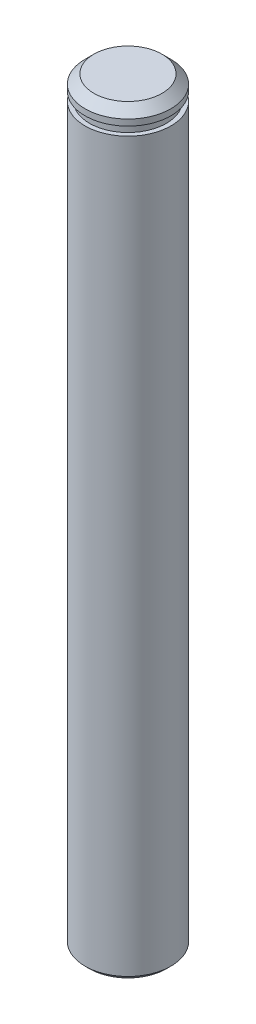
SolidWorks part; units mm, degrees
ref_plane "Front Plane" through (0, 0, 0) normal (0, 0, 1) x (1, 0, 0)
ref_plane "Top Plane" through (0, 0, 0) normal (0, 1, 0) x (1, 0, 0)
ref_plane "Right Plane" through (0, 0, 0) normal (1, 0, 0) x (0, 0, -1)
sketch "Sketch1" plane through (0, 0, 0) normal (0, 0, 1) x (1, 0, 0)
  line L0 (0, 41.165) -> (0, -40.665)
  line L1 (0, 41.165) -> (-0.5, 41.165)
  line L2 (-0.5, 41.165) -> (-0.5, 42.145)
  line L3 (-0.5, 42.145) -> (0, 42.145)
  line L4 (0, 42.145) -> (0, 42.835)
  line L5 (0, 42.835) -> (-1, 43.835)
  line L6 (-1, 43.835) -> (-4.825, 43.835)
  line L7 (-4.825, 43.835) -> (-4.825, -41.165)
  line L8 (-4.825, -41.165) -> (-0.5, -41.165)
  line L9 (0, -40.665) -> (-0.5, -41.165)
  point P1 (0, -41.165)
  dimension "D1" = 1
  dimension "D2" = 4.325
  dimension "D3" = 0.69
  dimension "D4" = 0.98
  dimension "D5" = 0.5
  dimension "D6" = 45
  dimension "D7" = 85
  dimension "D8" = 0.5
  dimension "D9" = 45
revolve "Revolve1" add sketch "Sketch1" angle 360 about L7
